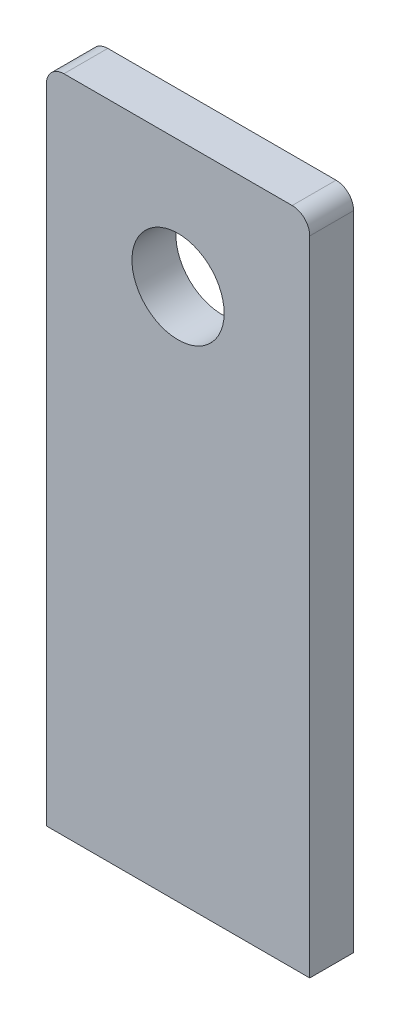
SolidWorks part; units mm, degrees
material "Plain Carbon Steel"
ref_plane "Front Plane" through (0, 0, 0) normal (0, 0, 1) x (1, 0, 0)
ref_plane "Top Plane" through (0, 0, 0) normal (0, 1, 0) x (1, 0, 0)
ref_plane "Right Plane" through (0, 0, 0) normal (1, 0, 0) x (0, 0, -1)
sketch "Sketch1" plane through (0, 0, 0) normal (0, 0, 1) x (1, 0, 0)
  line L1 (-15, 37.6) -> (15, 37.6)
  line L2 (-15, 37.6) -> (-15, -37.6)
  line L3 (-15, -37.6) -> (15, -37.6)
  line L4 (15, 37.6) -> (15, -37.6)
  line L5 (-15, 37.6) -> (15, -37.6) construction
  line L6 (-15, -37.6) -> (15, 37.6) construction
  circle A0 centre (0, 23.1) radius 5.25
  point P0 (0, 0)
  point P8 (0, 0)
  dimension "D3" = 10.5
  dimension "D1" = 30
  dimension "D2" = 75.2
  dimension "D4" = 14.5
extrude "Boss-Extrude1" add sketch "Sketch1" along normal mid plane 5
fillet "Fillet1" radius 2 2 edges at (15, 37.6, 0) (-15, 37.6, 0)
